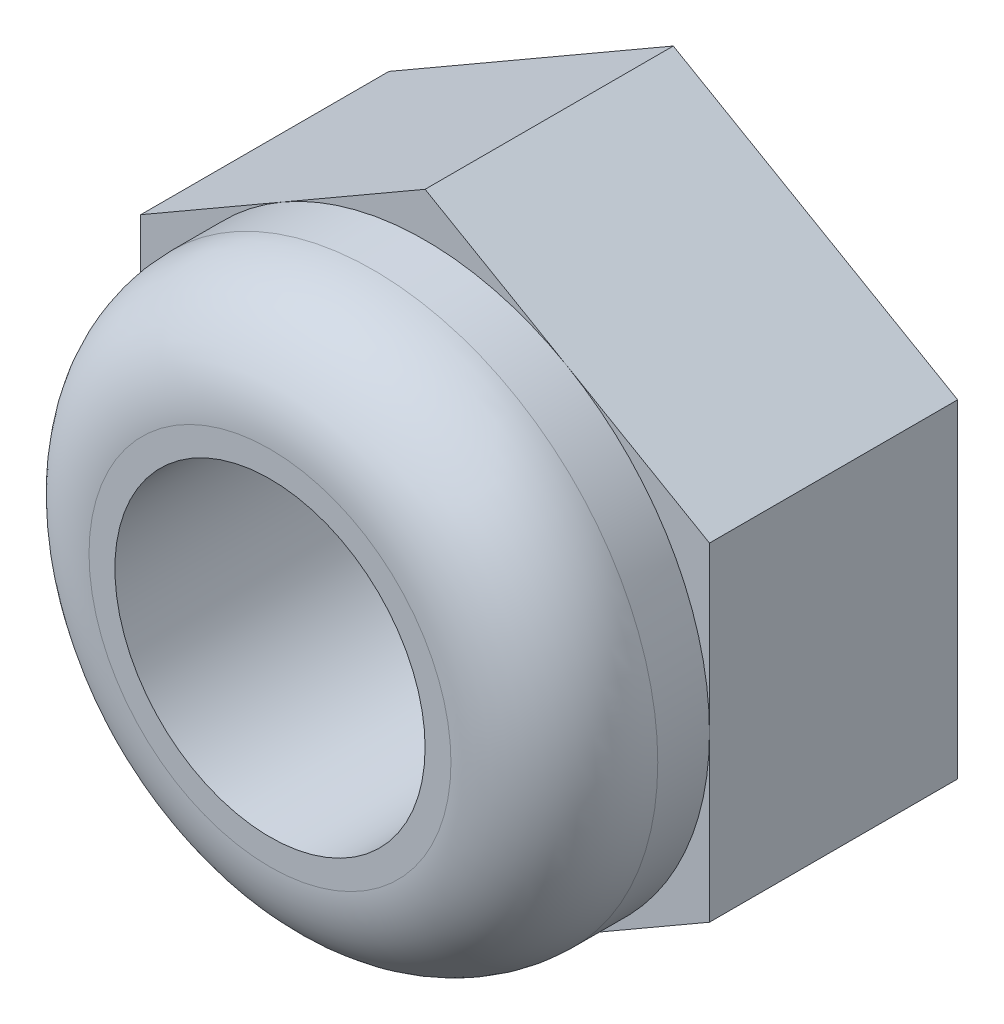
SolidWorks part; units mm, degrees
material "AISI 304"
ref_plane "Front Plane" through (0, 0, 0) normal (0, 0, 1) x (1, 0, 0)
ref_plane "Top Plane" through (0, 0, 0) normal (0, 1, 0) x (1, 0, 0)
ref_plane "Right Plane" through (0, 0, 0) normal (1, 0, 0) x (0, 0, -1)
sketch "草图2" plane through (0, 0, 0) normal (0, 0, 1) x (1, 0, 0)
  line L1 (2.75, -1.5877) -> (2.75, 1.5877)
  line L2 (2.75, 1.5877) -> (0, 3.1754)
  line L3 (0, 3.1754) -> (-2.75, 1.5877)
  line L4 (-2.75, 1.5877) -> (-2.75, -1.5877)
  line L5 (-2.75, -1.5877) -> (0, -3.1754)
  line L6 (0, -3.1754) -> (2.75, -1.5877)
  circle A0 centre (0, 0) radius 2.75 construction
  dimension "D1" = 5.5
extrude "凸台-拉伸1" add sketch "草图2" along normal blind 2.4
sketch "草图3" plane through (0, 0, 2.4) normal (0, 0, 1) x (1, 0, 0)
  line L1 (0, 3.1754) -> (-2.75, 1.5877) construction
  circle A0 centre (0, 0) radius 2.75
extrude "凸台-拉伸2" add sketch "草图3" along normal blind 1.5
fillet "圆角1" radius 1 1 edges at (2.75, 0, 3.9)
sketch "草图4" plane through (0, 0, 3.9) normal (0, 0, 1) x (1, 0, 0)
  circle A0 centre (0, 0) radius 1.5
  dimension "D1" = 3
extrude "切除-拉伸1" cut sketch "草图4" against normal blind 9.5
